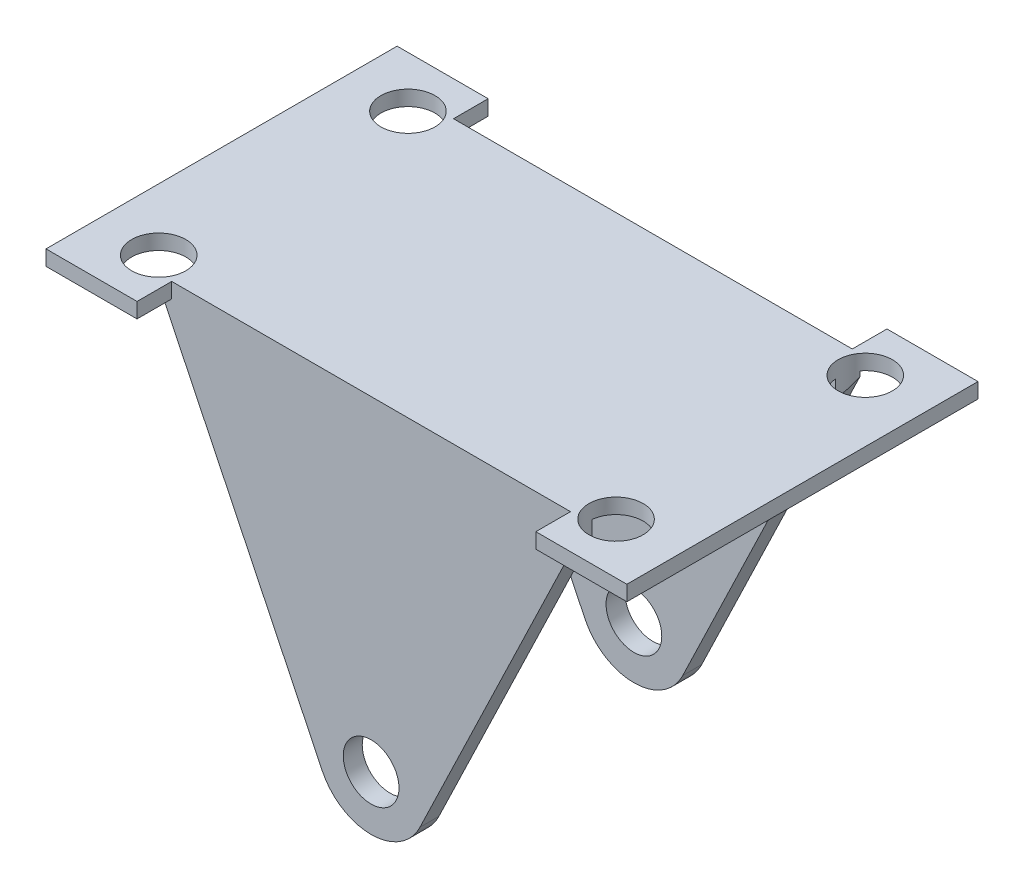
SolidWorks part; units mm, degrees
material "Plain Carbon Steel"
ref_plane "Front Plane" through (0, 0, 0) normal (0, 0, 1) x (1, 0, 0)
ref_plane "Top Plane" through (0, 0, 0) normal (0, 1, 0) x (1, 0, 0)
ref_plane "Right Plane" through (0, 0, 0) normal (1, 0, 0) x (0, 0, -1)
sketch "Sketch1" plane through (0, 0, 0) normal (0, 0, 1) x (1, 0, 0)
  line L0 (0, 19.05) -> (0, -19.05) construction
  line L1 (25.4, 19.05) -> (-25.4, 19.05)
  line L2 (-25.4, 19.05) -> (-5.7209, -21.8056)
  line L3 (5.7209, -21.8056) -> (25.4, 19.05)
  arc A1 (-5.7209, -21.8056) -> (5.7209, -21.8056) centre (0, -19.05) ccw
  point P5 (0, 19.05)
  point P8 (0, 0)
  dimension "D2" = 6.35
  dimension "D1" = 50.8
  dimension "D3" = 38.1
  dimension "D4" = 64.281
extrude "Boss-Extrude1" add sketch "Sketch1" along normal mid plane 33.02 contours L2 A1 L3 L1
sketch "Sketch2" plane through (0, 19.05, 0) normal (0, 1, 0) x (1, 0, 0)
  line L0 (-34.036, -20.574) -> (-34.036, 20.574)
  line L1 (-34.036, 20.574) -> (-23.368, 20.574)
  line L2 (-23.368, 20.574) -> (-23.368, 16.51)
  line L3 (25.4, 16.51) -> (-25.4, 16.51) construction
  line L4 (-23.368, 16.51) -> (23.368, 16.51)
  line L5 (0, 0) -> (-68.072, 0) construction
  line L6 (25.4, -16.51) -> (-25.4, -16.51) construction
  line L7 (23.368, -16.51) -> (-23.368, -16.51)
  line L8 (-23.368, -16.51) -> (-23.368, -20.574)
  line L9 (-23.368, -20.574) -> (-34.036, -20.574)
  line L10 (0, -20.8736) -> (0, 33.7864) construction
  line L11 (23.368, 20.574) -> (23.368, 16.51)
  line L12 (34.036, 20.574) -> (23.368, 20.574)
  line L13 (23.368, -20.574) -> (34.036, -20.574)
  line L14 (23.368, -16.51) -> (23.368, -20.574)
  line L15 (34.036, -20.574) -> (34.036, 20.574)
  point P3 (-34.036, 0)
  point P21 (0, 16.51)
  point P26 (0, -16.51)
  dimension "D1" = 34.036
  dimension "D2" = 4.064
  dimension "D3" = 10.668
extrude "Boss-Extrude2" add sketch "Sketch2" against normal blind 1.778
sketch "Sketch3" plane through (0, 0, 0) normal (0, 0, 1) x (1, 0, 0)
  circle A0 centre (0, -19.05) radius 24.511
  dimension "D1" = 49.022
extrude "Boss-Extrude3" [suppressed] add sketch "Sketch3" along normal mid plane 21.844
hole_wizard "1/4 (0.25) Diameter Hole1" positions "Sketch4" profile "Sketch5" hole size "1/4" standard "ANSI Inch" end condition through all
sketch "Sketch4" plane through (0, 19.05, 0) normal (0, 1, 0) x (1, 0, 0)
  line L0 (-26.797, 14.6038) -> (-26.797, -14.6038) construction
  line L2 (-26.797, -14.6038) -> (26.797, -14.6038) construction
  line L3 (26.797, -14.6038) -> (26.797, 14.6038) construction
  line L4 (26.797, 14.6038) -> (-26.797, 14.6038) construction
  point P0 (-26.797, 14.6038)
  point P2 (-26.797, -14.6038)
  point P8 (-26.797, 0)
  point P15 (26.797, -14.6038)
  point P18 (26.797, 14.6038)
  point P25 (0, 14.6038)
  dimension "D1" = 29.2077
  dimension "D2" = 53.594
sketch "Sketch5" plane through (-26.797, 19.05, -14.6038) normal (1, 0, 0) x (0, 0, 1)
  line L0 (0, 0) -> (0, 44.45)
  line L1 (0, 44.45) -> (3.175, 44.45)
  line L2 (3.175, 44.45) -> (3.175, 0)
  line L5 (3.175, 0) -> (0, 0)
  line L11 (0, -6.35) -> (0, 107.95) construction
  dimension "Thru Hole Dia." = 6.35
  dimension "Thru Hole Depth" = 44.45
sketch "Sketch6" plane through (0, 0, 0) normal (0, 0, 1) x (1, 0, 0)
  line L0 (23.368, 17.272) -> (34.036, 17.272) construction
  line L1 (-26.9875, -27.178) -> (26.9875, -27.178)
  line L2 (-26.9875, -27.178) -> (-26.9875, 17.272)
  line L3 (-26.9875, 17.272) -> (26.9875, 17.272)
  line L4 (26.9875, -27.178) -> (26.9875, 17.272)
  line L5 (-26.9875, -27.178) -> (26.9875, 17.272) construction
  line L6 (-26.9875, 17.272) -> (26.9875, -27.178) construction
  point P0 (0, -4.953)
  dimension "D1" = 44.45
  dimension "D2" = 53.975
extrude "Cut-Extrude1" cut sketch "Sketch6" against normal mid plane 28.575
hole_wizard "F (0.257) Diameter Hole1" positions "Sketch7" profile "Sketch8" hole size "F" standard "ANSI Inch" end condition through all
sketch "Sketch7" plane through (0, 0, 16.51) normal (0, 0, 1) x (1, 0, 0)
  point P0 (0, -19.05)
sketch "Sketch8" plane through (0, -19.05, 16.51) normal (1, 0, 0) x (0, -1, 0)
  line L0 (0, 0) -> (0, 37.084)
  line L1 (0, 37.084) -> (3.2639, 37.084)
  line L2 (3.2639, 37.084) -> (3.2639, 0)
  line L5 (3.2639, 0) -> (0, 0)
  line L11 (0, -6.35) -> (0, 107.95) construction
  dimension "Thru Hole Dia." = 6.5278
  dimension "Thru Hole Depth" = 37.084
